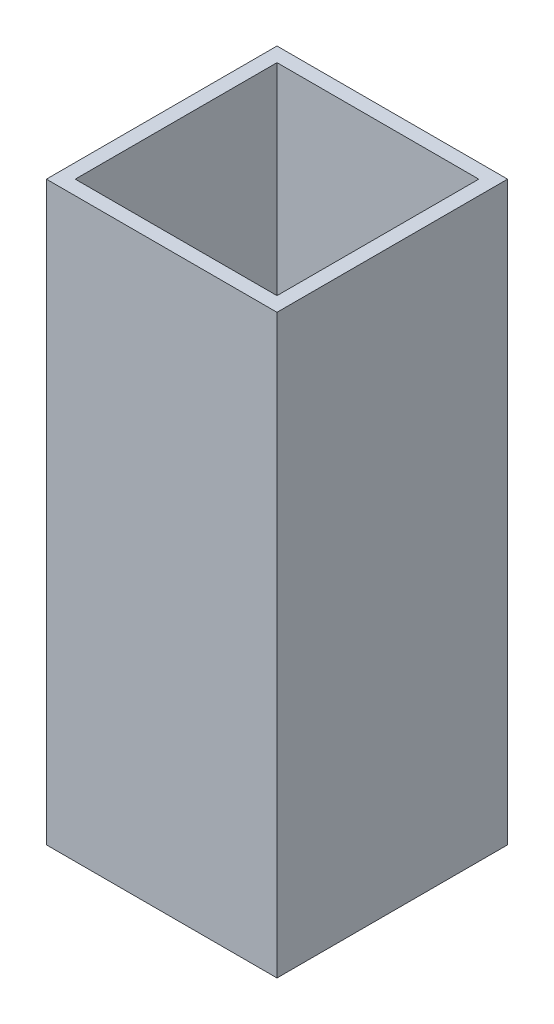
SolidWorks part; units mm, degrees
material "6061 Alloy"
ref_plane "Front Plane" through (0, 0, 0) normal (0, 0, 1) x (1, 0, 0)
ref_plane "Top Plane" through (0, 0, 0) normal (0, 1, 0) x (1, 0, 0)
ref_plane "Right Plane" through (0, 0, 0) normal (1, 0, 0) x (0, 0, -1)
sketch "Sketch1" plane through (0, 0, 0) normal (0, 1, 0) x (1, 0, 0)
  line L1 (-12.7, -12.7) -> (12.7, -12.7)
  line L2 (-12.7, -12.7) -> (-12.7, 12.7)
  line L3 (-12.7, 12.7) -> (12.7, 12.7)
  line L4 (12.7, -12.7) -> (12.7, 12.7)
  line L7 (-11.1125, -11.1125) -> (11.1125, -11.1125)
  line L8 (-11.1125, -11.1125) -> (-11.1125, 11.1125)
  line L9 (-11.1125, 11.1125) -> (11.1125, 11.1125)
  line L10 (11.1125, -11.1125) -> (11.1125, 11.1125)
  point P6 (0, 0)
  dimension "D1" = 25.4
  dimension "D2" = 25.4
  dimension "D3" = 1.5875
  dimension "D4" = 1.5875
  dimension "D5" = 1.5875
extrude "Boss-Extrude1" add sketch "Sketch1" along normal blind 63.5
